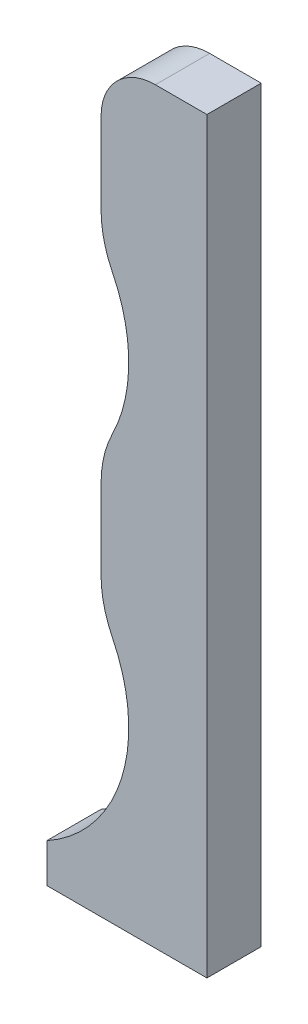
SolidWorks part; units mm, degrees
ref_plane "Front Plane" through (0, 0, 0) normal (0, 0, 1) x (1, 0, 0)
ref_plane "Top Plane" through (0, 0, 0) normal (0, 1, 0) x (1, 0, 0)
ref_plane "Right Plane" through (0, 0, 0) normal (1, 0, 0) x (0, 0, -1)
sketch "Sketch1" plane through (0, 0, 0) normal (0, 0, 1) x (1, 0, 0)
  line L0 (3237.7278, 2688.297) -> (3237.7278, 2644.5678)
  line L1 (3237.7278, 2688.297) -> (3234.713, 2688.297)
  line L2 (3237.7278, 2644.5678) -> (3228.363, 2644.5678)
  line L3 (3228.363, 2644.5678) -> (3228.363, 2646.8412)
  line L4 (3231.538, 2661.8659) -> (3231.538, 2666.5332)
  line L5 (3231.538, 2680.3698) -> (3231.538, 2685.122)
  arc A0 (3228.363, 2646.8412) -> (3232.1964, 2659.0502) centre (3223.9038, 2654.9476) ccw
  arc A1 (3231.538, 2661.8659) -> (3232.1964, 2659.0502) centre (3237.888, 2661.8659) ccw
  arc A2 (3232.1964, 2669.349) -> (3232.1964, 2677.5541) centre (3223.9038, 2673.4515) ccw
  arc A3 (3231.538, 2680.3698) -> (3232.1964, 2677.5541) centre (3237.888, 2680.3698) ccw
  arc A4 (3232.1964, 2669.349) -> (3231.538, 2666.5332) centre (3237.888, 2666.5332) ccw
  arc A5 (3234.713, 2688.297) -> (3231.538, 2685.122) centre (3234.713, 2685.122) ccw
extrude "Boss-Extrude1" add sketch "Sketch1" along normal blind 3.175
